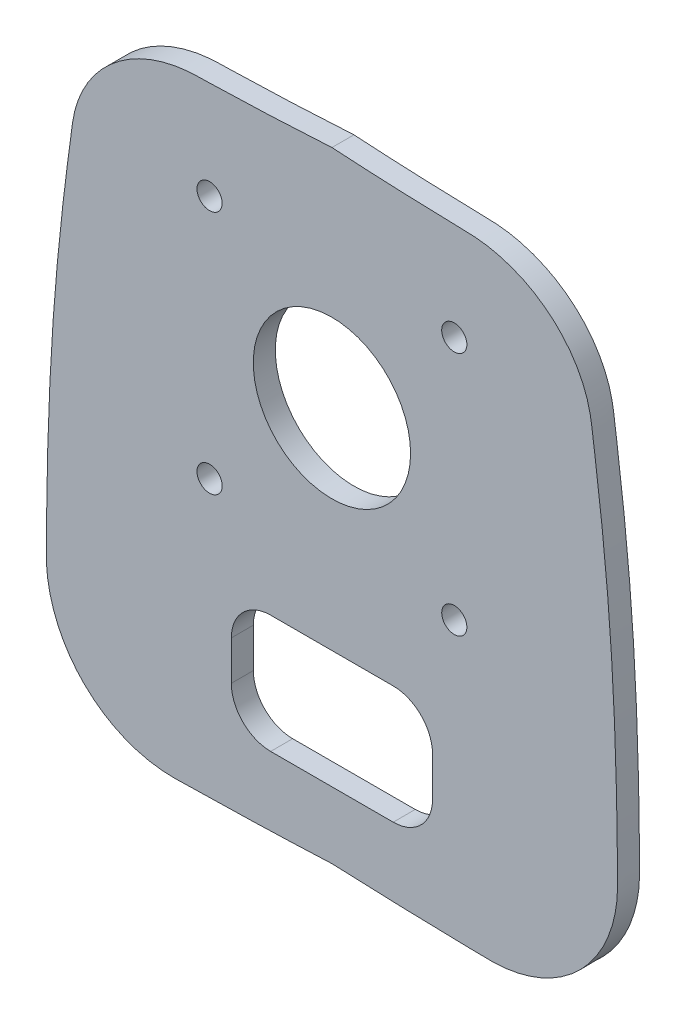
SolidWorks part; units mm, degrees
material "Фанера"
ref_plane "Front Plane" through (0, 0, 0) normal (0, 0, 1) x (1, 0, 0)
ref_plane "Top Plane" through (0, 0, 0) normal (0, 1, 0) x (1, 0, 0)
ref_plane "Right Plane" through (0, 0, 0) normal (1, 0, 0) x (0, 0, -1)
sketch "Эскиз1" plane through (0, 0, 0) normal (0, 0, 1) x (1, 0, 0)
  line L0 (-21.5194, 103.6369) -> (27.4484, 103.6369) construction
  line L1 (-7.7912, 61.934) -> (7.7912, 61.934)
  line L2 (-12.7912, 66.934) -> (-12.7912, 71.934)
  line L3 (-7.7912, 76.934) -> (7.7912, 76.934)
  line L4 (12.7912, 66.934) -> (12.7912, 71.934)
  line L5 (-12.7912, 61.934) -> (12.7912, 76.934) construction
  line L6 (-12.7912, 76.934) -> (12.7912, 61.934) construction
  line L7 (-0.0002, 124.7406) -> (-0.0006, 82.156) construction
  line L8 (-0.0005, 89.269) -> (-0.0012, 29.2446) construction
  line L9 (-16.3852, 87.2517) -> (20.6174, 124.2543) construction
  circle A0 centre (15.5563, 119.1933) radius 1.6
  circle A1 centre (0, 103.6369) radius 5.3081 construction
  circle A2 centre (0, 103.6369) radius 10
  arc A3 (7.7912, 61.934) -> (12.7912, 66.934) centre (7.7912, 66.934) ccw
  arc A4 (7.7912, 76.934) -> (12.7912, 71.934) centre (7.7912, 71.934) cw
  arc A5 (-7.7912, 61.934) -> (-12.7912, 66.934) centre (-7.7912, 66.934) cw
  arc A6 (-12.7912, 71.934) -> (-7.7912, 76.934) centre (-7.7912, 71.934) cw
  circle A7 centre (-15.5568, 119.1936) radius 1.6
  circle A8 centre (-15.5568, 88.0803) radius 1.6
  circle A9 centre (15.5563, 88.0806) radius 1.6
  spline S0 degree 3 poles (0, 137.8141) (-0.0001, 137.7355) (-0.0002, 137.579) (0.0001, 137.3088) (0.0001, 137.0122) (0, 136.6854) (0.0001, 136.3275) (0.0002, 135.6489) (-0.0002, 134.5096) (0, 132.7957) (-0.0002, 131.0209) (0.0003, 129.3815) (-0.0008, 127.524) (0, 125.8466) (-0.0002, 124.5355) (0.0001, 123.7391) (0.0008, 122.9083) (0.0013, 122.0409) (-0.0024, 121.1363) (-0.0032, 120.1919) (0.014, 119.2132) (0.0045, 118.5173) (-0.0002, 118.1731) knots 0 0 0 0 0.049195 0.097914 0.146095 0.193678 0.240603 0.286814 0.434432 0.571578 0.649741 0.723036 0.791276 0.854427 0.874299 0.893649 0.912499 0.930877 0.948815 0.966303 0.983333 1 1 1 1 construction
  spline S2 degree 3 poles (0, 131.5214) (-0.6758, 131.4803) (-2.0048, 131.3993) (-4.6641, 131.2544) (-7.3131, 131.1293) (-9.9748, 131.0225) (-11.9636, 130.9521) (-13.9615, 130.8905) (-15.5414, 130.8503) (-16.7205, 130.8224) (-17.4919, 130.8101) (-18.2904, 130.7596) (-19.1141, 130.6683) (-20.3289, 130.472) (-21.9294, 130.0705) (-24.4092, 129.1089) (-27.3366, 127.2929) (-29.628, 124.8065) (-31.0358, 122.3951) (-31.6408, 120.8748) (-31.9623, 119.6713) (-32.1031, 118.9995) (-32.2005, 118.3557) (-32.2879, 117.7092) (-32.3822, 117.0268) (-32.5665, 115.6676) (-32.8362, 113.6255) (-33.1778, 110.8916) (-33.548, 107.727) (-33.9372, 104.0668) (-34.3136, 99.9941) (-34.6384, 95.8408) (-34.8987, 91.7616) (-35.1099, 87.5964) (-35.2661, 83.5871) (-35.3868, 79.4206) (-35.4525, 76.0703) (-35.4918, 73.2049) (-35.5096, 71.3201) (-35.5204, 69.8566) (-35.5231, 68.7838) (-35.4757, 67.9133) (-35.3144, 66.5149) (-34.9563, 64.8397) (-34.2441, 62.8406) (-33.284, 60.9807) (-32.0659, 59.2493) (-30.6387, 57.7195) (-28.9998, 56.3923) (-27.2027, 55.3117) (-25.2663, 54.4865) (-23.5853, 54.0286) (-22.2047, 53.7995) (-21.3257, 53.7129) (-20.5943, 53.6772) (-20.0262, 53.6682) (-19.4398, 53.6792) (-18.8352, 53.6888) (-18.2123, 53.7004) (-17.5714, 53.713) (-16.433, 53.7368) (-15.1488, 53.7663) (-13.7386, 53.8) (-12.3123, 53.8351) (-10.5565, 53.8815) (-8.4408, 53.944) (-6.3422, 54.0137) (-4.2029, 54.0914) (-2.0892, 54.1743) (-0.68, 54.2395) (0, 54.271) knots 0 0 0 0 0.015371 0.030225 0.060457 0.075573 0.090697 0.105634 0.120948 0.126574 0.132408 0.13846 0.144729 0.151213 0.166386 0.182085 0.211454 0.243779 0.257622 0.274709 0.28071 0.285892 0.290281 0.295488 0.300701 0.305919 0.326626 0.347461 0.368464 0.398955 0.431018 0.461309 0.493524 0.523806 0.555981 0.584606 0.618431 0.63205 0.649659 0.661218 0.665276 0.674012 0.680989 0.69722 0.71277 0.729036 0.744579 0.760685 0.776373 0.792303 0.808131 0.824011 0.831719 0.839883 0.844043 0.848342 0.852779 0.857355 0.862069 0.86692 0.871907 0.887919 0.89608 0.90393 0.920308 0.935952 0.951979 0.967975 0.984548 1 1 1 1 construction
  spline S3 degree 3 poles (0, 54.271) (0.4369, 54.2505) (1.3313, 54.2084) (2.7044, 54.1506) (4.3256, 54.0869) (6.1773, 54.0195) (8.2238, 53.951) (10.2853, 53.8891) (11.9958, 53.8433) (13.3827, 53.8086) (14.4215, 53.7836) (15.458, 53.7592) (16.6295, 53.7326) (17.907, 53.7058) (19.2805, 53.6808) (20.5277, 53.6625) (21.6489, 53.7371) (22.6745, 53.8689) (23.6786, 54.0663) (25.0067, 54.421) (26.6258, 55.0339) (29.0501, 56.3516) (31.7066, 58.6088) (33.6412, 61.4838) (34.7018, 64.0278) (35.148, 65.675) (35.3817, 67.0504) (35.4806, 67.9937) (35.5313, 69.0526) (35.5161, 70.1025) (35.5106, 71.2126) (35.5016, 72.1633) (35.493, 72.9906) (35.4845, 73.6962) (35.4692, 74.8586) (35.4443, 76.4343) (35.3891, 79.1954) (35.2619, 83.9854) (34.9747, 90.8845) (34.4149, 99.1518) (33.7474, 106.0319) (33.1057, 111.5184) (32.7094, 114.6013) (32.4339, 116.647) (32.3193, 117.4868) (32.2271, 118.1487) (32.1605, 118.6442) (32.069, 119.1673) (31.9294, 119.8055) (31.6975, 120.6441) (31.2299, 121.9321) (30.3025, 123.7617) (28.7446, 125.8237) (26.6972, 127.6595) (24.5914, 128.9716) (22.5464, 129.8615) (20.8742, 130.3505) (19.5067, 130.6147) (18.4575, 130.7485) (17.4536, 130.8139) (16.5192, 130.826) (15.6421, 130.8482) (14.808, 130.8688) (13.9835, 130.8914) (13.1683, 130.9152) (11.2538, 130.9749) (8.9184, 131.0615) (6.1715, 131.183) (4.1238, 131.2841) (2.0706, 131.3953) (0.6982, 131.4789) (0, 131.5214) knots 0 0 0 0 0.009929 0.020328 0.031198 0.046762 0.062391 0.077684 0.093582 0.101236 0.109177 0.117172 0.124772 0.135779 0.146179 0.155964 0.16408 0.171662 0.179425 0.187293 0.202851 0.218591 0.249771 0.28093 0.296251 0.312207 0.31954 0.327909 0.333721 0.343597 0.351736 0.358925 0.36518 0.370516 0.374945 0.39157 0.406292 0.437639 0.500347 0.563035 0.625721 0.657255 0.688434 0.696281 0.704114 0.707676 0.711452 0.715465 0.719728 0.726277 0.735201 0.750797 0.772664 0.793449 0.812883 0.82873 0.843943 0.85233 0.860329 0.867937 0.875154 0.881542 0.887855 0.894095 0.900266 0.906368 0.937579 0.95332 0.968788 0.98412 1 1 1 1 construction
  spline S4 degree 1 poles (0, 132.3229) (-0.0003, 53.4702) knots 0 0 1 1 construction
  spline S5 degree 1 poles (-0.0003, 53.4702) (0, 132.3229) knots 0 0 1 1 construction
  spline S6 degree 3 poles (0, 132.3229) (-1.3718, 132.2393) (-4.1159, 132.0788) (-8.2336, 131.8882) (-11.666, 131.759) (-14.4146, 131.68) (-16.1261, 131.6313) (-17.5115, 131.6138) (-18.9641, 131.5138) (-21.4516, 131.1083) (-24.8803, 129.8732) (-28.4941, 127.364) (-30.8293, 124.5186) (-32.1364, 121.8974) (-32.6962, 120.1627) (-32.9664, 118.703) (-33.1422, 117.3418) (-33.3804, 115.6319) (-33.6467, 113.581) (-33.9907, 110.8428) (-34.5501, 106.0454) (-35.2157, 99.1744) (-35.7745, 90.9092) (-36.0612, 84.0161) (-36.2081, 78.501) (-36.2685, 75.0539) (-36.3022, 72.2975) (-36.3124, 70.5714) (-36.3292, 69.1994) (-36.2823, 67.7358) (-35.9494, 65.2377) (-34.7922, 61.7687) (-32.3552, 58.121) (-29.0186, 55.2586) (-25.6991, 53.7196) (-22.8688, 53.0539) (-21.071, 52.8714) (-19.6219, 52.872) (-18.2603, 52.9003) (-15.837, 52.9473) (-12.4016, 53.0306) (-6.8869, 53.1838) (-2.7546, 53.3426) (-0.0003, 53.4702) knots -0.000369 -0.000369 -0.000369 -0.000369 0.030884 0.062137 0.093389 0.109016 0.124642 0.132455 0.140268 0.155895 0.187147 0.2184 0.249653 0.265279 0.280905 0.288719 0.296532 0.312158 0.327784 0.343411 0.374664 0.437169 0.499674 0.56218 0.593432 0.624685 0.640311 0.655938 0.663751 0.671564 0.687191 0.718443 0.749696 0.780949 0.812201 0.827828 0.843454 0.851267 0.85908 0.874707 0.905959 0.937212 0.999717 0.999717 0.999717 0.999717
  spline S7 degree 3 poles (-0.0003, 53.4702) (2.7541, 53.3407) (6.8885, 53.1839) (12.3985, 53.0312) (15.8451, 52.9453) (18.5916, 52.8971) (20.6923, 52.8378) (22.8737, 53.053) (25.6947, 53.7198) (29.0166, 55.2561) (32.3623, 58.1265) (34.8014, 61.7884) (35.9542, 65.2517) (36.2828, 67.7579) (36.3305, 69.2103) (36.3106, 70.5942) (36.3029, 72.3121) (36.2677, 75.0713) (36.2078, 78.5171) (36.0606, 84.0323) (35.7736, 90.9255) (35.2143, 99.1905) (34.5484, 106.0614) (33.9888, 110.8587) (33.6446, 113.5968) (33.3786, 115.6475) (33.1394, 117.3584) (32.9656, 118.7194) (32.6911, 120.1781) (32.1309, 121.9118) (30.8198, 124.5317) (28.486, 127.371) (24.8791, 129.8736) (21.457, 131.1044) (18.5977, 131.5788) (16.4534, 131.6292) (14.4184, 131.6778) (11.6632, 131.7603) (8.2342, 131.8878) (4.1156, 132.0789) (1.3717, 132.2394) (0, 132.3229) knots 0.000283 0.000283 0.000283 0.000283 0.062788 0.094041 0.125293 0.14092 0.156546 0.172172 0.187799 0.219051 0.250304 0.281557 0.312809 0.328436 0.336249 0.344062 0.359689 0.375315 0.406568 0.43782 0.500326 0.562831 0.625336 0.656589 0.672216 0.687842 0.703468 0.711281 0.719095 0.734721 0.750347 0.7816 0.812853 0.844105 0.859732 0.875358 0.890984 0.906611 0.937863 0.969116 1.000369 1.000369 1.000369 1.000369
  point P7 (0, 69.434)
  dimension "D2" = 20
  dimension "D3" = 5
  dimension "D6" = 3.2
  dimension "D4" = 15
  dimension "D5" = 45
  dimension "D7" = 22
  dimension "D1" = 0.8
extrude "Бобышка-Вытянуть1" add sketch "Эскиз1" along normal mid plane 2.8
